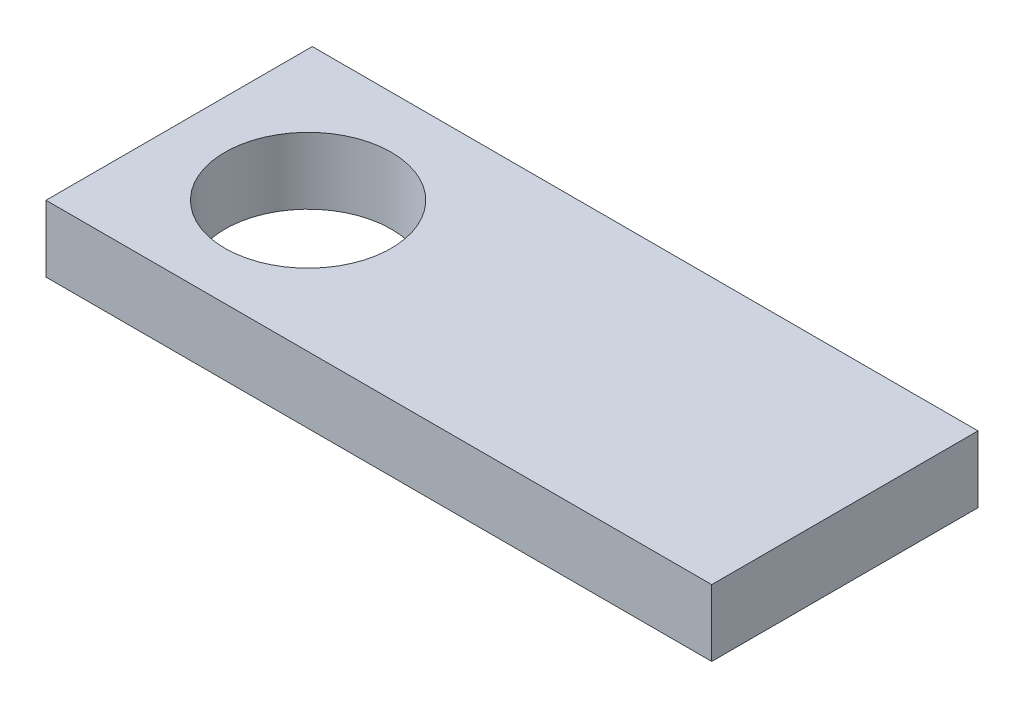
SolidWorks part; units mm, degrees
ref_plane "Front Plane" through (0, 0, 0) normal (0, 0, 1) x (1, 0, 0)
ref_plane "Top Plane" through (0, 0, 0) normal (0, 1, 0) x (1, 0, 0)
ref_plane "Right Plane" through (0, 0, 0) normal (1, 0, 0) x (0, 0, -1)
sketch "Sketch1" plane through (0, 0, 0) normal (0, 1, 0) x (1, 0, 0)
  line L1 (0, 0) -> (127, 0)
  line L2 (0, 0) -> (0, 50.8)
  line L3 (0, 50.8) -> (127, 50.8)
  line L4 (127, 0) -> (127, 50.8)
  dimension "D1" = 127
  dimension "D2" = 50.8
extrude "Boss-Extrude1" add sketch "Sketch1" along normal blind 12.7
sketch "Sketch2" plane through (0, 12.7, 0) normal (0, 1, 0) x (1, 0, 0)
  line L1 (0, 0) -> (25, 0)
  line L2 (0, 0) -> (0, 25)
  line L3 (0, 25) -> (25, 25)
  line L4 (25, 0) -> (25, 25)
  circle A0 centre (25, 25) radius 15.875
  dimension "D1" = 25
  dimension "D2" = 25
extrude "Cut-Extrude1" cut sketch "Sketch2" against normal blind 12.7 contours L4 A0 L3 | L3 A0 L4
